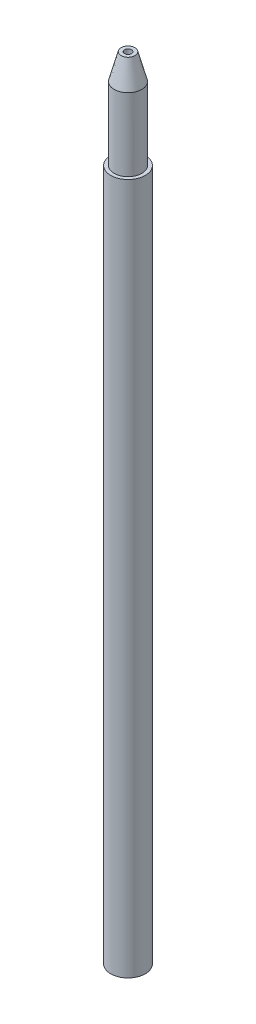
SolidWorks part; units mm, degrees
material "Fibreglass"
ref_plane "Plan de face" through (0, 0, 0) normal (0, 0, 1) x (1, 0, 0)
ref_plane "Plan de dessus" through (0, 0, 0) normal (0, 1, 0) x (1, 0, 0)
ref_plane "Plan de droite" through (0, 0, 0) normal (1, 0, 0) x (0, 0, -1)
sketch "Esquisse1" plane through (0, 0, 0) normal (0, 0, 1) x (1, 0, 0)
  line L0 (1, -35) -> (1, 193.5)
  line L1 (1, 193.5) -> (4, 193.5)
  line L2 (4, 193.5) -> (4, 165)
  line L3 (4, 165) -> (5, 165)
  line L4 (5, 165) -> (5, 20)
  line L6 (5, 20) -> (5, -35)
  line L7 (1, -35) -> (5, -35)
  line L8 (0, 0) -> (0, 5.8127) construction
  point P7 (3, -35)
  dimension "D1" = 1
  dimension "D2" = 5
  dimension "D4" = 200
  dimension "D5" = 4
  dimension "D7" = 28.5
revolve "Révolution1" add sketch "Esquisse1" angle 360 about L8
hole_wizard "Diamètre du perçage Ø3.0 (3)1" positions "Esquisse6" profile "Esquisse8" hole size "Ø3.0" standard "ISO"
sketch "Esquisse6" plane through (0, -35, 0) normal (0, -1, 0) x (-1, 0, 0)
  point P0 (0, 0)
sketch "Esquisse8" plane through (0, -35, 0) normal (1, 0, 0) x (0, 0, -1)
  line L0 (0, 0) -> (0, 40.9013)
  line L1 (0, 40.9013) -> (1.5, 40)
  line L2 (1.5, 40) -> (1.5, 0)
  line L5 (1.5, 0) -> (0, 0)
  line L10 (0, 40.9013) -> (-1.5, 40) construction
  line L11 (0, -6.35) -> (0, 107.95) construction
  dimension "Diamètre du perçage" = 3
  dimension "Profondeur du perçage" = 40
  dimension "Angle de pointe" = 118
chamfer "Chanfrein1" distance 2 angle 75 1 edges at (0, 193.5, -4)
